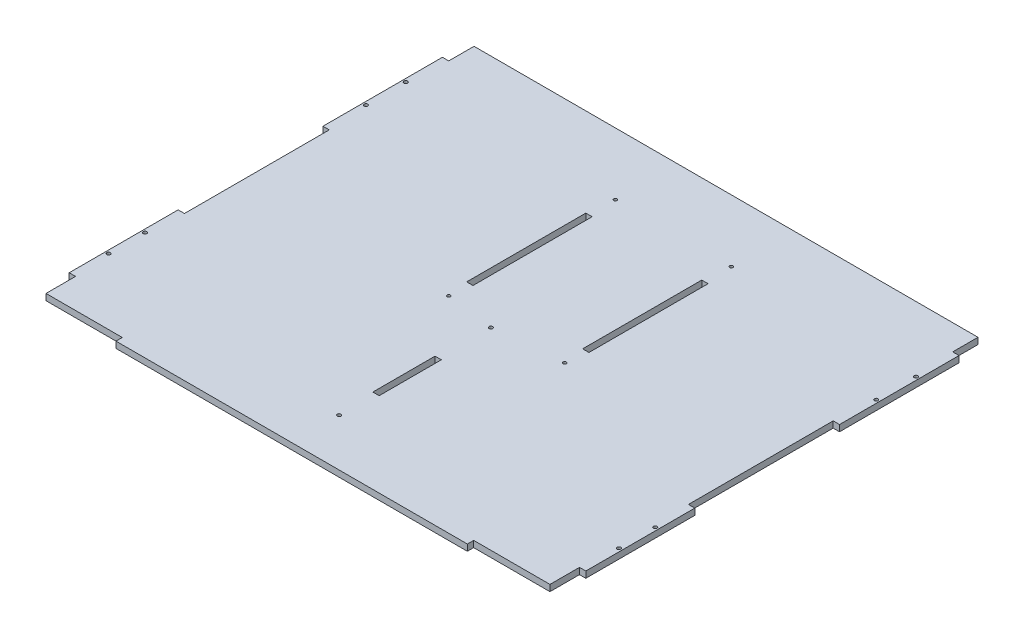
SolidWorks part; units mm, degrees
ref_plane "Front Plane" through (0, 0, 0) normal (0, 0, 1) x (1, 0, 0)
ref_plane "Top Plane" through (0, 0, 0) normal (0, 1, 0) x (1, 0, 0)
ref_plane "Right Plane" through (0, 0, 0) normal (1, 0, 0) x (0, 0, -1)
sketch "Sketch1" plane through (0, 0, 0) normal (0, 1, 0) x (1, 0, 0)
  line L1 (0, 0) -> (490, 0)
  line L2 (0, 0) -> (0, 411.98)
  line L3 (0, 411.98) -> (490, 411.98)
  line L4 (490, 0) -> (490, 411.98)
  dimension "D1" = 490
  dimension "D2" = 411.98
extrude "Boss-Extrude1" add sketch "Sketch1" along normal blind 6
sketch "Sketch2" plane through (0, 6, 0) normal (0, 1, 0) x (1, 0, 0)
  line L1 (0, 0) -> (78.3333, 0)
  line L2 (0, 0) -> (0, 6)
  line L3 (0, 6) -> (78.3333, 6)
  line L4 (78.3333, 0) -> (78.3333, 6)
  line L5 (490, 0) -> (411.6667, 0)
  line L6 (490, 0) -> (490, 6)
  line L7 (490, 6) -> (411.6667, 6)
  line L8 (411.6667, 0) -> (411.6667, 6)
  line L9 (0, 411.98) -> (0, 0) construction
  line L10 (0, 274.6533) -> (6, 274.6533)
  line L11 (0, 274.6533) -> (0, 137.3267)
  line L12 (0, 137.3267) -> (6, 137.3267)
  line L14 (6, 274.6533) -> (6, 137.3267)
  line L15 (490, 411.98) -> (0, 411.98) construction
  line L16 (490, 0) -> (490, 411.98) construction
  line L17 (490, 274.6533) -> (484, 274.6533)
  line L19 (490, 274.6533) -> (490, 137.3267)
  line L20 (490, 137.3267) -> (484, 137.3267)
  line L21 (484, 274.6533) -> (484, 137.3267)
  point P24 (78.3333, 3)
  dimension "D2" = 6
  dimension "D3" = 6
  dimension "D4" = 137.3267
  dimension "D5" = 137.3267
  dimension "D6" = 6
  dimension "D7" = 333.3333
extrude "Cut-Extrude1" cut sketch "Sketch2" against normal blind 12
sketch "Sketch4" plane through (0, 6, 0) normal (0, 1, 0) x (1, 0, 0)
  line L0 (6, 274.6533) -> (0, 274.6533) construction
  line L1 (0, 411.98) -> (6, 411.98)
  line L2 (0, 411.98) -> (0, 387.98)
  line L3 (0, 387.98) -> (6, 387.98)
  line L4 (6, 411.98) -> (6, 387.98)
  line L5 (490, 411.98) -> (484, 411.98)
  line L6 (490, 411.98) -> (490, 387.98)
  line L7 (490, 387.98) -> (484, 387.98)
  line L8 (484, 411.98) -> (484, 387.98)
  line L9 (490, 6) -> (484, 6)
  line L10 (490, 6) -> (490, 33.9967)
  line L11 (490, 33.9967) -> (484, 33.9967)
  line L12 (484, 6) -> (484, 33.9967)
  line L13 (0, 6) -> (6, 6)
  line L14 (0, 6) -> (0, 33.9967)
  line L15 (0, 33.9967) -> (6, 33.9967)
  line L16 (6, 6) -> (6, 33.9967)
  line L17 (0, 137.3267) -> (6, 137.3267) construction
  line L18 (484, 137.3267) -> (490, 137.3267) construction
  dimension "D1" = 6
  dimension "D2" = 6
  dimension "D3" = 6
  dimension "D4" = 6
  dimension "D5" = 103.33
  dimension "D6" = 24
  dimension "D7" = 24
  dimension "D8" = 103.33
  dimension "D9" = 113.3267
extrude "Cut-Extrude2" cut sketch "Sketch4" against normal blind 12
sketch "Sketch6" plane through (0, 6, 0) normal (0, 1, 0) x (1, 0, 0)
  line L0 (0, 137.3267) -> (0, 33.9967) construction
  line L1 (242, 138.97) -> (248, 138.97)
  line L2 (242, 138.97) -> (242, 80)
  line L3 (242, 80) -> (248, 80)
  line L4 (248, 138.97) -> (248, 80)
  line L5 (78.3333, 0) -> (411.6667, 0) construction
  dimension "D1" = 58.97
  dimension "D2" = 6
  dimension "D3" = 242
  dimension "D4" = 80
extrude "Cut-Extrude3" cut sketch "Sketch6" against normal through all
hole_wizard "M3 Clearance Hole1" positions "Sketch7" profile "Sketch8" hole size "M3" standard "ANSI Metric" end condition through all
sketch "Sketch7" plane through (0, 6, 0) normal (0, 1, 0) x (1, 0, 0)
  line L0 (0, 387.98) -> (0, 274.6533) construction
  line L1 (0, 387.98) -> (6, 387.98) construction
  line L2 (6, 274.6533) -> (0, 274.6533) construction
  line L3 (0, 137.3267) -> (0, 33.9967) construction
  line L4 (0, 137.3267) -> (6, 137.3267) construction
  line L5 (6, 33.9967) -> (0, 33.9967) construction
  line L6 (490, 274.6533) -> (490, 387.98) construction
  line L7 (490, 33.9967) -> (490, 137.3267) construction
  line L8 (248, 138.97) -> (242, 138.97) construction
  line L9 (242, 80) -> (248, 80) construction
  point P0 (3, 350.2033)
  point P2 (3, 312.43)
  point P11 (3, 102.8833)
  point P13 (3, 68.44)
  point P22 (487, 350.2033)
  point P27 (487, 312.43)
  point P29 (487, 102.8833)
  point P31 (487, 68.44)
  point P36 (245, 188.97)
  point P38 (245, 45)
  dimension "D1" = 3
  dimension "D2" = 3
  dimension "D3" = 37.7767
  dimension "D4" = 37.7767
  dimension "D5" = 3
  dimension "D6" = 3
  dimension "D7" = 34.4433
  dimension "D8" = 34.4433
  dimension "D9" = 3
  dimension "D10" = 3
  dimension "D11" = 3
  dimension "D12" = 3
  dimension "D13" = 50
  dimension "D14" = 35
sketch "Sketch8" plane through (3, 6, -350.2033) normal (1, 0, 0) x (0, 0, 1)
  line L0 (0, 0) -> (0, 6)
  line L1 (0, 6) -> (1.7, 6)
  line L2 (1.7, 6) -> (1.7, 0)
  line L5 (1.7, 0) -> (0, 0)
  line L11 (0, -6.35) -> (0, 107.95) construction
  dimension "Thru Hole Dia." = 3.4
  dimension "Thru Hole Depth" = 6
hole_wizard "Ø3.0mm Dowel Hole1" positions "Sketch9" profile "Sketch10" hole size "Ø3.0" standard "ANSI Metric" end condition through all
sketch "Sketch9" plane through (0, 6, 0) normal (0, 1, 0) x (1, 0, 0)
  line L0 (312, 387.98) -> (306, 387.98) construction
  line L1 (202, 387.98) -> (196, 387.98) construction
  point P0 (309, 352.98)
  point P2 (309, 194.98)
  point P4 (199, 352.98)
  point P6 (199, 194.98)
  point P11 (309, 387.98)
  point P14 (199, 387.98)
  dimension "D1" = 0
  dimension "D2" = 0
  dimension "D3" = 0
  dimension "D4" = 0
  dimension "D5" = 25
  dimension "D6" = 20
  dimension "D7" = 25
  dimension "D8" = 20
sketch "Sketch10" plane through (309, 6, -352.98) normal (1, 0, 0) x (0, 0, 1)
  line L0 (0, 0) -> (0, 6)
  line L1 (0, 6) -> (1.5, 6)
  line L2 (1.5, 6) -> (1.5, 0)
  line L5 (1.5, 0) -> (0, 0)
  line L11 (0, -6.35) -> (0, 107.95) construction
  dimension "Thru Hole Dia." = 3
  dimension "Thru Hole Depth" = 6
sketch "Sketch11" plane through (0, 0, 0) normal (0, -1, 0) x (1, 0, 0)
  line L1 (312, -214.98) -> (306, -214.98)
  line L2 (312, -214.98) -> (312, -327.98)
  line L3 (312, -327.98) -> (306, -327.98)
  line L4 (306, -214.98) -> (306, -327.98)
  line L5 (202, -214.98) -> (196, -214.98)
  line L6 (202, -214.98) -> (202, -327.98)
  line L7 (202, -327.98) -> (196, -327.98)
  line L8 (196, -214.98) -> (196, -327.98)
extrude "Cut-Extrude4" cut sketch "Sketch11" against normal up to next
